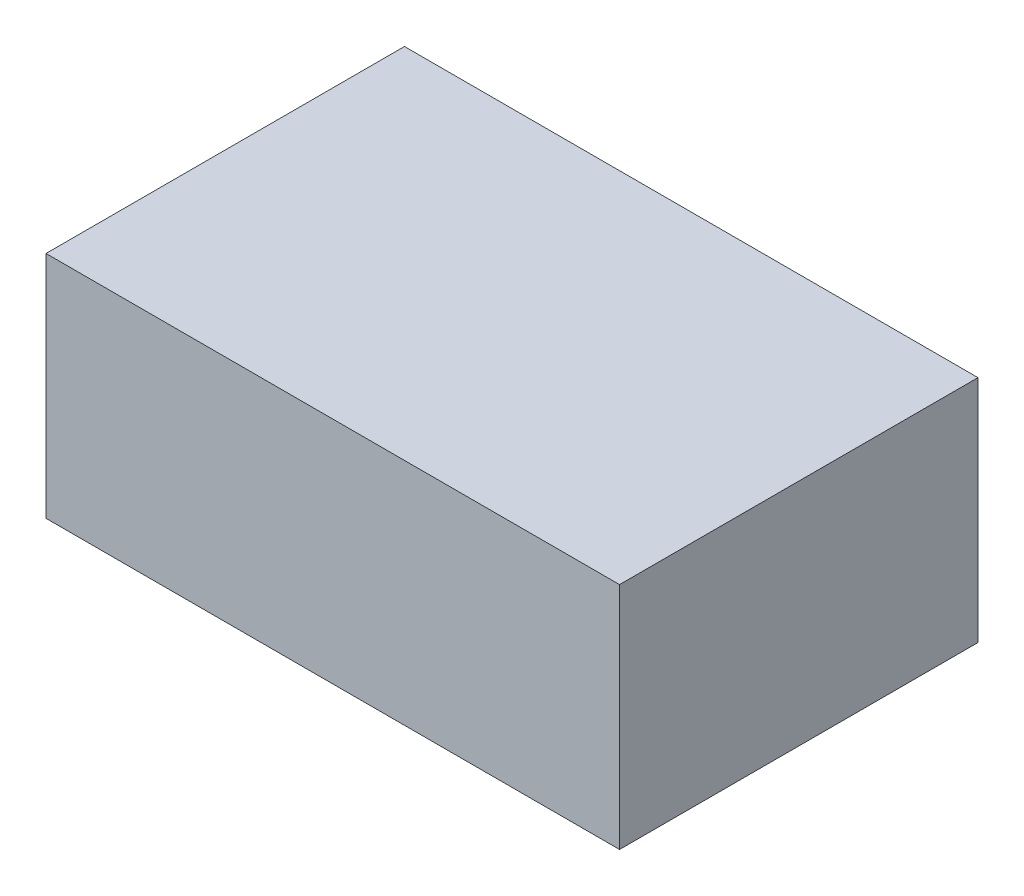
SolidWorks part; units mm, degrees
ref_plane "Front Plane" through (0, 0, 0) normal (0, 0, 1) x (1, 0, 0)
ref_plane "Top Plane" through (0, 0, 0) normal (0, 1, 0) x (1, 0, 0)
ref_plane "Right Plane" through (0, 0, 0) normal (1, 0, 0) x (0, 0, -1)
sketch "Sketch1" plane through (0, 0, 0) normal (0, 1, 0) x (1, 0, 0)
  line L1 (0, 0) -> (40, 0)
  line L2 (0, 0) -> (0, 25)
  line L3 (0, 25) -> (40, 25)
  line L4 (40, 0) -> (40, 25)
  dimension "D1" = 40
  dimension "D2" = 25
extrude "Boss-Extrude1" add sketch "Sketch1" along normal blind 16
